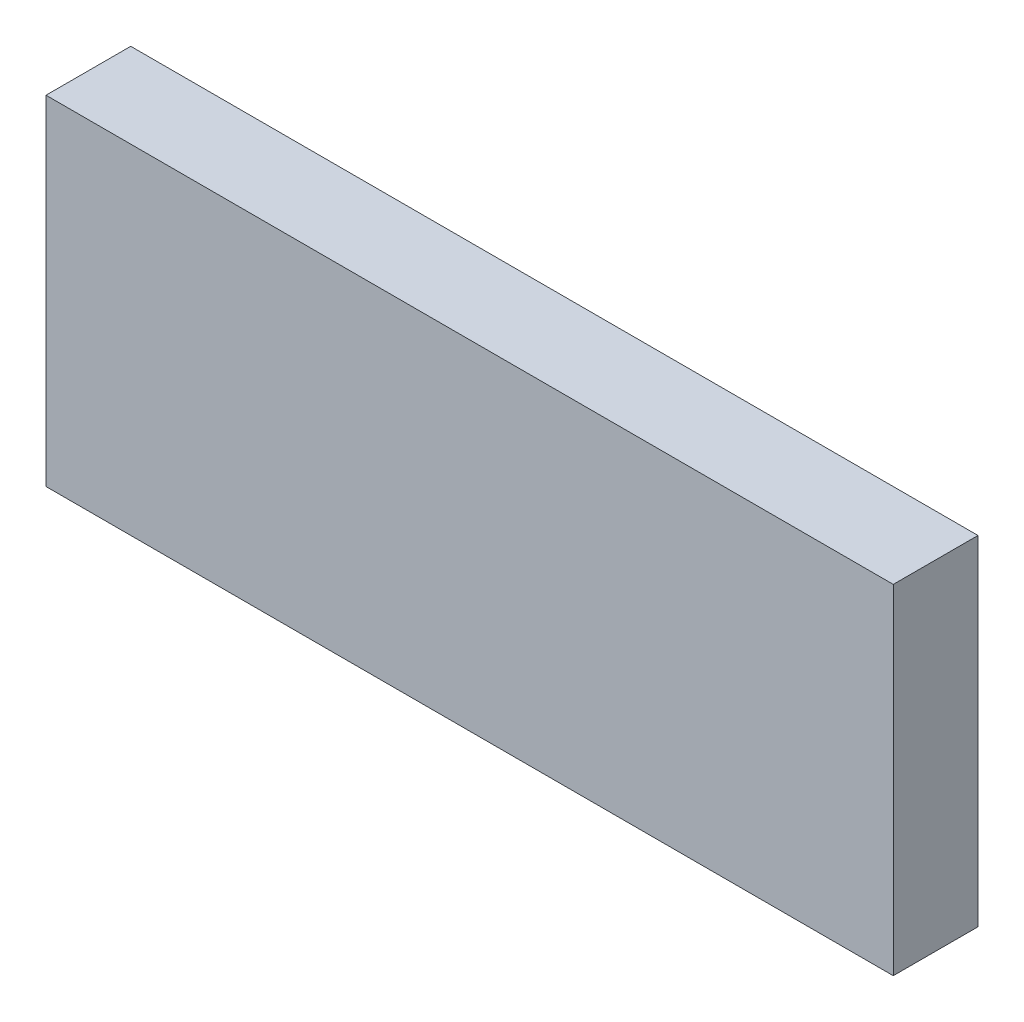
SolidWorks part; units mm, degrees
ref_plane "Face" through (0, 0, 0) normal (0, 0, 1) x (1, 0, 0)
ref_plane "Dessus" through (0, 0, 0) normal (0, 1, 0) x (1, 0, 0)
ref_plane "Droite" through (0, 0, 0) normal (1, 0, 0) x (0, 0, -1)
sketch "Esquisse1" plane through (0, 0, 0) normal (0, 0, 1) x (1, 0, 0)
  line L1 (141, -36.4613) -> (41, -36.4613)
  line L2 (141, -36.4613) -> (141, 3.5387)
  line L3 (141, 3.5387) -> (41, 3.5387)
  line L4 (41, -36.4613) -> (41, 3.5387)
  dimension "D1" = 100
  dimension "D2" = 40
extrude "Base-Extrusion" add sketch "Esquisse1" along normal blind 10
